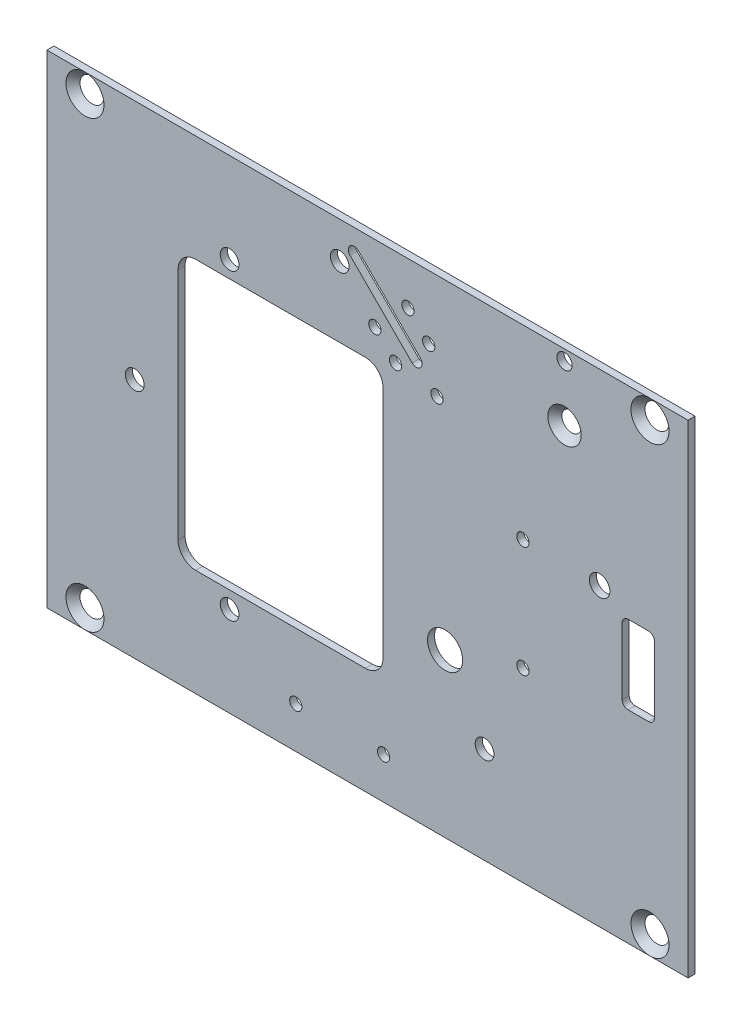
SolidWorks part; units mm, degrees
ref_plane "Front Plane" through (0, 0, 0) normal (0, 0, 1) x (1, 0, 0)
ref_plane "Top Plane" through (0, 0, 0) normal (0, 1, 0) x (1, 0, 0)
ref_plane "Right Plane" through (0, 0, 0) normal (1, 0, 0) x (0, 0, -1)
sketch "Sketch1" plane through (0, 0, 0) normal (0, 0, 1) x (1, 0, 0)
  line L1 (-54.75, -0.5) -> (54.75, -0.5)
  line L2 (-54.75, -0.5) -> (-54.75, -83)
  line L3 (-54.75, -83) -> (54.75, -83)
  line L4 (54.75, -0.5) -> (54.75, -83)
  line L5 (52.75, 0) -> (52.75, -83) construction
  line L6 (-54.75, -41.75) -> (54.75, -41.75) construction
  circle A0 centre (-23.55, -67.625) radius 1.6
  circle A1 centre (-23.55, -15.875) radius 1.6
  circle A2 centre (-4.75, -6.75) radius 1.6
  circle A3 centre (-39.75, -41.75) radius 1.6
  circle A4 centre (19.9987, -66.4987) radius 1.6
  circle A5 centre (-12.25, -75.9286) radius 1.05
  circle A6 centre (2.75, -75.9286) radius 1.05
  circle A7 centre (26.5429, -51.25) radius 1.05
  circle A8 centre (26.5429, -32.25) radius 1.05
  circle A9 centre (39.65, -32.5) radius 1.75
  dimension "D6" = 25.875
  dimension "D8" = 3.2
  dimension "D9" = 3.2
  dimension "D2" = 3.2
  dimension "D3" = 3.2
  dimension "D10" = 3.2
  dimension "D17" = 2.1
  dimension "D18" = 2.1
  dimension "D19" = 2.1
  dimension "D20" = 2.1
  dimension "D21" = 15
  dimension "D22" = 19
  dimension "D23" = 42.5
  dimension "D24" = 34.1786
  dimension "D25" = 28.2071
  dimension "D30" = 3.5
  dimension "D1" = 2
  dimension "D4" = 31.2
  dimension "D5" = 25.875
  dimension "D7" = 31.2
  dimension "D11" = 15
  dimension "D12" = 9.5
  dimension "D13" = 35
  dimension "D14" = 50
  dimension "D15" = 34.7513
  dimension "D16" = 24.7487
  dimension "D26" = 50.5
  dimension "D27" = 109.5
  dimension "D28" = 82.5
  dimension "D29" = 94.4
extrude "Boss-Extrude1" add sketch "Sketch1" along normal blind 1.2
hole_wizard "CSK for M3 Flat Countersunk Head Screw1" positions "Sketch4" profile "Sketch3" countersink size "M3" standard "JIS" end condition up to next
sketch "Sketch4" plane through (0, 0, 1.2) normal (0, 0, 1) x (1, 0, 0)
  line L0 (-54.75, -0.5) -> (-54.75, -83) construction
  line L3 (54.75, -83) -> (54.75, -0.5) construction
  line L4 (-54.75, -41.75) -> (54.75, -41.75) construction
  point P0 (-48.25, -3.75)
  point P1 (-48.25, -79.75)
  point P3 (48.25, -79.75)
  point P5 (48.25, -3.75)
  dimension "D1" = 6.5
  dimension "D2" = 38
  dimension "D3" = 6.5
  dimension "D4" = 38
  dimension "D5" = 38
  dimension "D6" = 6.5
  dimension "D7" = 6.5
  dimension "D8" = 38
sketch "Sketch3" plane through (-48.25, -3.75, 1.2) normal (1, 0, 0) x (0, -1, 0)
  line L0 (0, 0) -> (0, 1.2)
  line L1 (0, 1.2) -> (1.6, 1.2)
  line L2 (1.6, 1.2) -> (1.6, 1.65)
  line L3 (1.6, 1.65) -> (3.25, 0)
  line L5 (3.25, 0) -> (0, 0)
  line L6 (-1.6, 1.65) -> (-3.25, 0) construction
  line L11 (0, -6.35) -> (0, 107.95) construction
  dimension "Thru Hole Dia." = 3.2
  dimension "Thru Hole Depth" = 1.2
  dimension "Near C'Sink Dia." = 6.5
  dimension "Near C'Sink Angle" = 90
hole_wizard "CSK for M2.5 Flat Countersunk Head Screw1" positions "Sketch6" profile "Sketch5" countersink size "M2.5" standard "JIS" end condition up to next
sketch "Sketch6" plane through (0, 0, 1.2) normal (0, 0, 1) x (1, 0, 0)
  line L4 (54.75, -83) -> (54.75, -0.5) construction
  line L5 (54.75, -41.75) -> (-54.75, -41.75) construction
  line L6 (-54.75, -0.5) -> (-54.75, -83) construction
  point P0 (33.65, -11.85)
  dimension "D1" = 29.9
  dimension "D2" = 21.1
sketch "Sketch5" plane through (33.65, -11.85, 1.2) normal (1, 0, 0) x (0, -1, 0)
  line L0 (0, 0) -> (0, 1.2)
  line L1 (0, 1.2) -> (1.35, 1.2)
  line L2 (1.35, 1.2) -> (1.35, 1.5)
  line L3 (1.35, 1.5) -> (2.85, 0)
  line L5 (2.85, 0) -> (0, 0)
  line L6 (-1.35, 1.5) -> (-2.85, 0) construction
  line L11 (0, -6.35) -> (0, 107.95) construction
  dimension "Thru Hole Dia." = 2.7
  dimension "Thru Hole Depth" = 1.2
  dimension "Near C'Sink Dia." = 5.7
  dimension "Near C'Sink Angle" = 90
hole_wizard "Ø2.6 (2.6) Diameter Hole1" positions "Sketch8" profile "Sketch7" hole size "Ø2.6" standard "Ansi Metric" end condition up to next
sketch "Sketch8" plane through (0, 0, 1.2) normal (0, 0, 1) x (1, 0, 0)
  line L2 (54.75, -83) -> (54.75, -0.5) construction
  circle A1 centre (33.65, -11.85) radius 1.65 construction
  point P0 (33.65, -2.32)
  dimension "D2" = 9.53
  dimension "D1" = 21.1
sketch "Sketch7" plane through (33.65, -2.32, 1.2) normal (1, 0, 0) x (0, -1, 0)
  line L0 (0, 0) -> (0, 1.2)
  line L1 (0, 1.2) -> (1.3, 1.2)
  line L2 (1.3, 1.2) -> (1.3, 0)
  line L5 (1.3, 0) -> (0, 0)
  line L11 (0, -6.35) -> (0, 107.95) construction
  dimension "Thru Hole Dia." = 2.6
  dimension "Thru Hole Depth" = 1.2
sketch "Sketch9" plane through (0, 0, 1.2) normal (0, 0, 1) x (1, 0, 0)
  line L1 (-32.35, -64.75) -> (2.65, -64.75)
  line L2 (-32.35, -64.75) -> (-32.35, -18.75)
  line L3 (-32.35, -18.75) -> (2.65, -18.75)
  line L4 (2.65, -64.75) -> (2.65, -18.75)
  line L5 (-32.35, -64.75) -> (2.65, -18.75) construction
  line L6 (-32.35, -18.75) -> (2.65, -64.75) construction
  line L7 (8.3315, -14.8817) -> (-2.2751, -4.2751) construction
  line L8 (7.6244, -15.5888) -> (-2.9822, -4.9822)
  line L9 (9.0386, -14.1746) -> (-1.568, -3.568)
  line L10 (-54.75, -41.75) -> (54.75, -41.75) construction
  line L11 (43.5, -35.05) -> (49, -35.05)
  line L13 (54.75, -83) -> (54.75, -0.5) construction
  line L14 (43.5, -35.05) -> (43.5, -48.45)
  line L15 (43.5, -48.45) -> (49, -48.45)
  line L16 (49, -35.05) -> (49, -48.45)
  line L17 (-54.75, -41.75) -> (-4.75, -41.75) construction
  line L19 (1.2604, -13.4675) -> (4.0888, -10.6391) construction
  line L20 (4.7959, -17.003) -> (7.6244, -14.1746) construction
  line L21 (11.867, -18.4173) -> (8.3315, -14.8817) construction
  line L23 (4.0888, -10.6391) -> (6.9173, -7.8107) construction
  line L24 (7.6244, -14.1746) -> (10.4528, -11.3462) construction
  line L25 (-54.75, -0.5) -> (-54.75, -83) construction
  arc A0 (7.6244, -15.5888) -> (9.0386, -14.1746) centre (8.3315, -14.8817) ccw
  arc A1 (-1.568, -3.568) -> (-2.9822, -4.9822) centre (-2.2751, -4.2751) ccw
  circle A2 centre (1.2604, -13.4675) radius 1.05
  circle A3 centre (6.9173, -7.8107) radius 1.05
  circle A4 centre (10.4528, -11.3462) radius 1.05
  circle A5 centre (13.25, -55.25) radius 3
  circle A6 centre (4.7959, -17.003) radius 1.05
  circle A8 centre (11.867, -18.4173) radius 1.05
  point P0 (-14.85, -41.75)
  point P9 (3.0282, -9.5784)
  dimension "D4" = 1
  dimension "D9" = 2.1
  dimension "D10" = 5.5
  dimension "D16" = 6
  dimension "D2" = 23
  dimension "D3" = 10.1
  dimension "D5" = 13.4
  dimension "D6" = 6.7
  dimension "D7" = 5.75
  dimension "D8" = 15
  dimension "D11" = 22.4
  dimension "D12" = 52.4749
  dimension "D13" = 37.4749
  dimension "D14" = 46
  dimension "D15" = 35
  dimension "D17" = 13.5
  dimension "D18" = 68
extrude "Cut-Extrude1" cut sketch "Sketch9" against normal up to next
fillet "Fillet1" radius 3 4 edges at (2.65, -18.75, 0.6) (2.65, -64.75, 0.6) (-32.35, -64.75, 0.6) (-32.35, -18.75, 0.6)
fillet "Fillet2" radius 1 4 edges at (43.5, -48.45, 0.6) (49, -48.45, 0.6) (43.5, -35.05, 0.6) (49, -35.05, 0.6)
sketch "Sketch10" plane through (0, 0, 0) normal (0, 0, -1) x (-1, 0, 0)
  line L0 (54.75, -0.5) -> (54.75, -83) construction
  line L1 (-8.5, -64) -> (-14.5, -64)
  line L2 (-8.5, -64) -> (-8.5, -70)
  line L3 (-8.5, -70) -> (-14.5, -70)
  line L4 (-14.5, -64) -> (-14.5, -70)
  line L5 (-8.5, -64) -> (-14.5, -70) construction
  line L6 (-8.5, -70) -> (-14.5, -64) construction
  line L7 (54.75, -83) -> (-54.75, -83) construction
  point P0 (-11.5, -67)
  dimension "D1" = 66.25
  dimension "D2" = 16
  dimension "D3" = 6
  dimension "D4" = 6
extrude "Boss-Extrude2" add sketch "Sketch10" along normal blind 10
